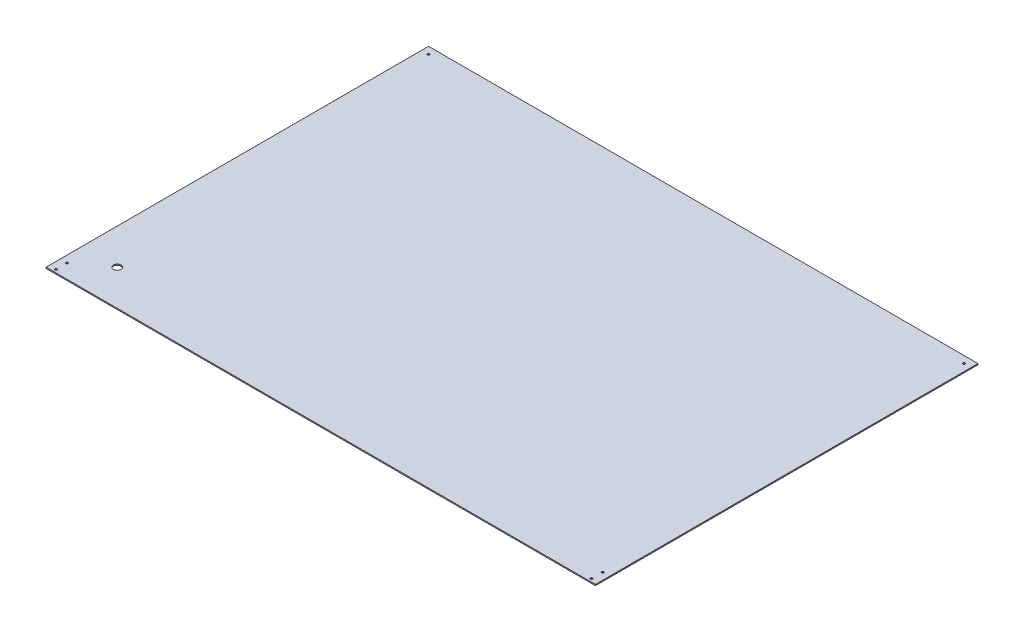
SolidWorks part; units mm, degrees
material "Acrylic (Medium-high impact)"
ref_plane "Front Plane" through (0, 0, 0) normal (0, 0, 1) x (1, 0, 0)
ref_plane "Top Plane" through (0, 0, 0) normal (0, 1, 0) x (1, 0, 0)
ref_plane "Right Plane" through (0, 0, 0) normal (1, 0, 0) x (0, 0, -1)
sketch "Sketch1" plane through (0, 0, 0) normal (0, 1, 0) x (1, 0, 0)
  line L1 (-790, -550) -> (790, -550) construction
  line L2 (-790, -550) -> (-790, 550) construction
  line L3 (-790, 550) -> (790, 550) construction
  line L4 (790, -550) -> (790, 550) construction
  line L5 (-790, -550) -> (790, 550) construction
  line L6 (-790, 550) -> (790, -550) construction
  point P0 (0, 0)
  dimension "Length" = 1580
  dimension "Width" = 1100
sketch "Sketch2" plane through (0, 0, 0) normal (1, 0, 0) x (0, 0, -1)
  line L1 (-550, -1.5875) -> (550, -1.5875) construction
  line L2 (-550, -1.5875) -> (-550, 1.5875) construction
  line L3 (-550, 1.5875) -> (550, 1.5875) construction
  line L4 (550, -1.5875) -> (550, 1.5875) construction
  line L5 (-550, -1.5875) -> (550, 1.5875) construction
  line L6 (-550, 1.5875) -> (550, -1.5875) construction
  dimension "Thickness" = 3.175
sketch "Sketch3" plane through (0, 0, 0) normal (1, 0, 0) x (0, 0, -1)
  line L1 (550, 1.5875) -> (-550, 1.5875)
  line L2 (550, 1.5875) -> (550, -1.5875)
  line L3 (550, -1.5875) -> (-550, -1.5875)
  line L4 (-550, 1.5875) -> (-550, -1.5875)
extrude "Boss-Extrude1" add sketch "Sketch3" against normal up to vertex (790 mm away) and the other way up to vertex (790 mm away) up to point (-790, 0, -550) other way up to point (790, 0, -550)
sketch "Sketch4" plane through (0, 1.5875, 0) normal (0, 1, 0) x (1, 0, 0)
  line L0 (-790, -550) -> (790, -550) construction
  line L1 (-790, 550) -> (-790, -550) construction
  circle A0 centre (-687.6, -447.6) radius 11
  dimension "D1" = 22
  dimension "D2" = 102.4
  dimension "D3" = 102.4
extrude "Cut-Extrude1" cut sketch "Sketch4" against normal blind 10
sketch "Sketch5" plane through (0, -1.5875, 0) normal (0, -1, 0) x (-1, 0, 0)
  line L0 (790, 550) -> (-790, 550) construction
  line L1 (790, -550) -> (790, 550) construction
  line L2 (0, 159.2994) -> (0, 550) construction
  circle A0 centre (770, 530) radius 3.175
  circle A1 centre (-770, 530) radius 3.175
  dimension "D1" = 6.35
  dimension "D2" = 20
  dimension "D3" = 20
extrude "Cut-Extrude2" cut sketch "Sketch5" against normal blind 10
sketch "Sketch6" plane through (0, 1.5875, 0) normal (0, 1, 0) x (1, 0, 0)
  line L0 (-770, -542.8694) -> (-770, -500) construction
  line L1 (-790, -550) -> (-750, -550)
  line L2 (-790, -550) -> (-790, -500)
  line L5 (-753.392, -525) -> (-790, -525) construction
  line L6 (0, -381.8206) -> (0, 550) construction
  line L7 (-790, 550) -> (790, 550) construction
  circle A0 centre (-770, -509) radius 3.175
  circle A1 centre (-770, -541) radius 3.175
  circle A2 centre (770, -509) radius 3.175
  circle A3 centre (770, -541) radius 3.175
  dimension "D3" = 6.35
  dimension "D4" = 32
extrude "Cut-Extrude3" cut sketch "Sketch6" against normal blind 10 contours A0 | A1 | A3 | A2
